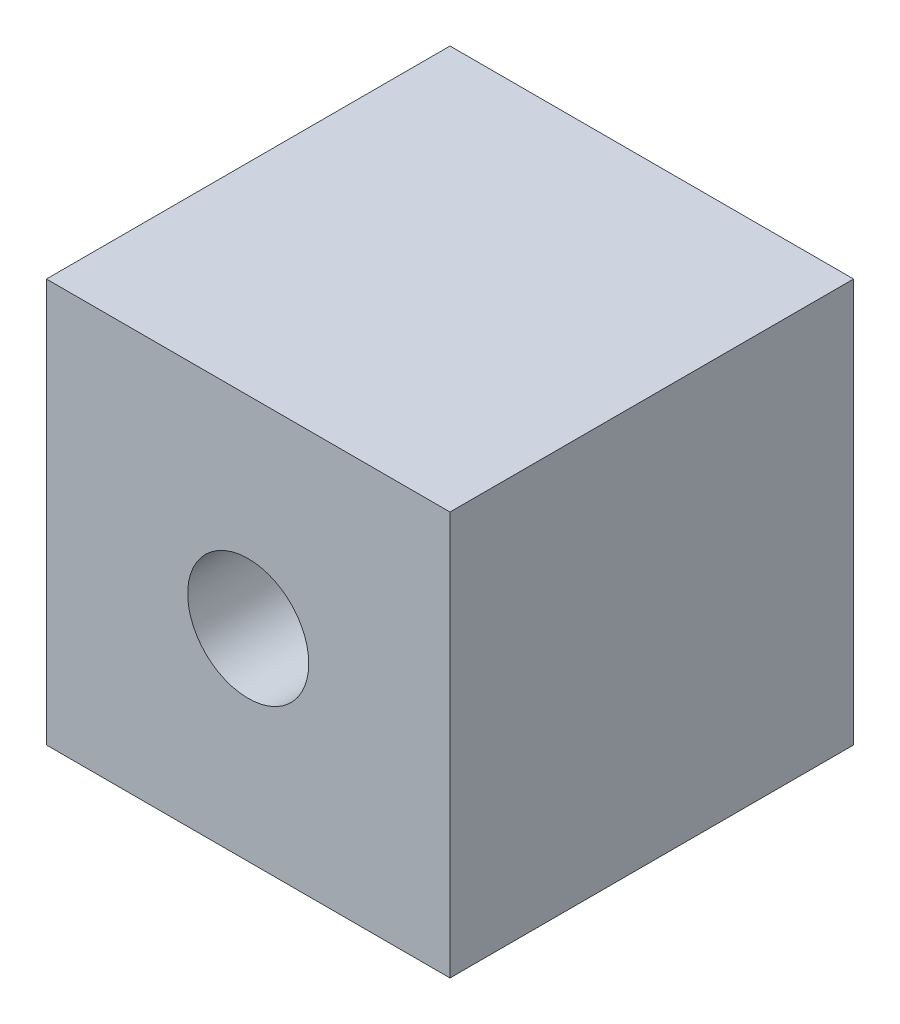
SolidWorks part; units mm, degrees
ref_plane "Front Plane" through (0, 0, 0) normal (0, 0, 1) x (1, 0, 0)
ref_plane "Top Plane" through (0, 0, 0) normal (0, 1, 0) x (1, 0, 0)
ref_plane "Right Plane" through (0, 0, 0) normal (1, 0, 0) x (0, 0, -1)
sketch "Sketch1" plane through (0, 0, 0) normal (0, 0, 1) x (1, 0, 0)
  line L1 (0, 0) -> (10, 0)
  line L2 (0, 0) -> (0, 10)
  line L3 (0, 10) -> (10, 10)
  line L4 (10, 0) -> (10, 10)
extrude "Boss-Extrude1" add sketch "Sketch1" along normal blind 10
sketch "Sketch2" plane through (0, 0, 0) normal (0, 0, 1) x (1, 0, 0)
  circle A0 centre (5, 5) radius 1.5
extrude "Cut-Extrude1" cut sketch "Sketch2" along normal through all
